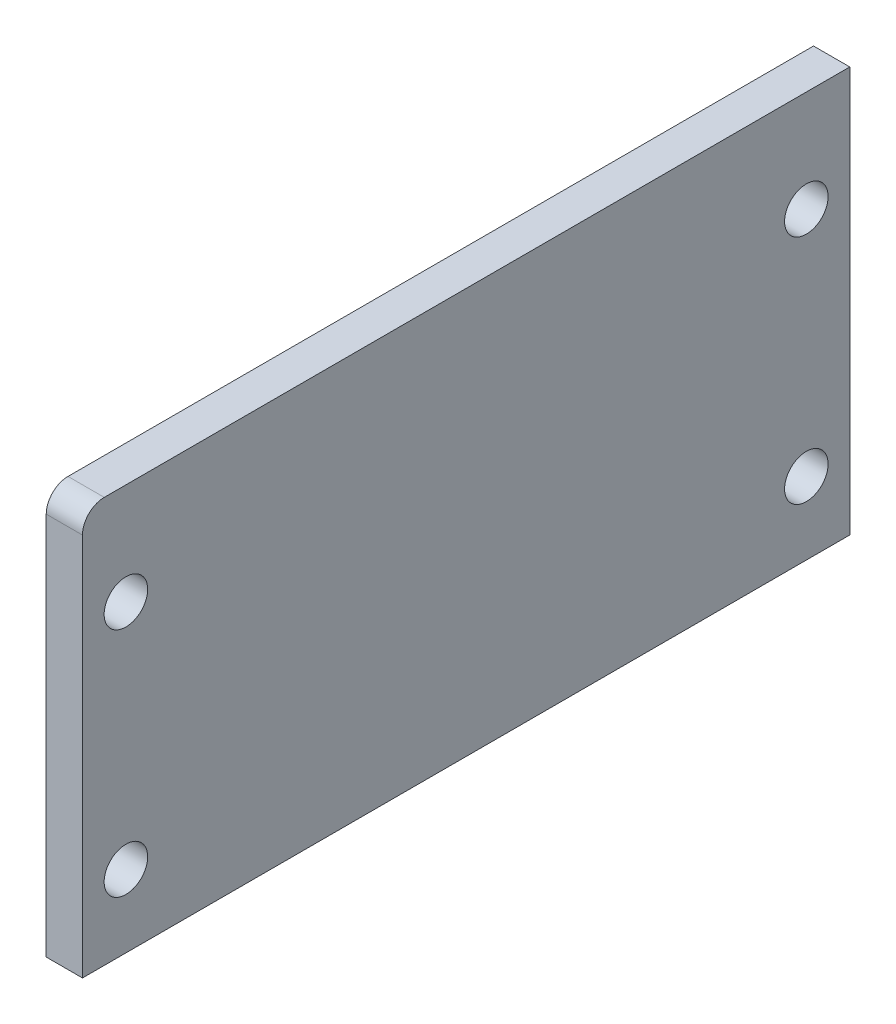
SolidWorks part; units mm, degrees
ref_plane "Front Plane" through (0, 0, 0) normal (0, 0, 1) x (1, 0, 0)
ref_plane "Top Plane" through (0, 0, 0) normal (0, 1, 0) x (1, 0, 0)
ref_plane "Right Plane" through (0, 0, 0) normal (1, 0, 0) x (0, 0, -1)
sketch "Sketch1" plane through (0, 0, 0) normal (1, 0, 0) x (0, 0, -1)
  line L1 (0, 0) -> (-67.31, 0)
  line L2 (0, 0) -> (0, 35.56)
  line L3 (0, 35.56) -> (-65.4, 35.56)
  line L4 (-67.31, 0) -> (-67.31, 33.65)
  arc A0 (-65.4, 35.56) -> (-67.31, 33.65) centre (-65.4, 33.65) ccw
  dimension "D3" = 1.91
  dimension "D1" = 67.31
  dimension "D2" = 35.56
extrude "Boss-Extrude1" add sketch "Sketch1" along normal blind 3.18 contours A0 L4 L1 L2 L3
sketch "Sketch2" plane through (3.18, 0, 0) normal (1, 0, 0) x (0, 0, -1)
  line L0 (0, 0) -> (0, 35.56) construction
  line L1 (0, 0) -> (-67.31, 0) construction
  circle A0 centre (-63.5, 26.67) radius 1.91
  circle A1 centre (-63.5, 6.35) radius 1.91
  circle A2 centre (-3.81, 6.35) radius 1.91
  circle A3 centre (-3.81, 26.67) radius 1.91
  dimension "D2" = 3.82
  dimension "D3" = 3.82
  dimension "D6" = 3.81
  dimension "D7" = 6.35
  dimension "D8" = 26.67
  dimension "D10" = 6.35
  dimension "D4" = 3.82
  dimension "D13" = 3.82
  dimension "D5" = 3.81
  dimension "D9" = 63.5
  dimension "D11" = 63.5
  dimension "D12" = 26.67
extrude "Cut-Extrude4" cut sketch "Sketch2" against normal through all
